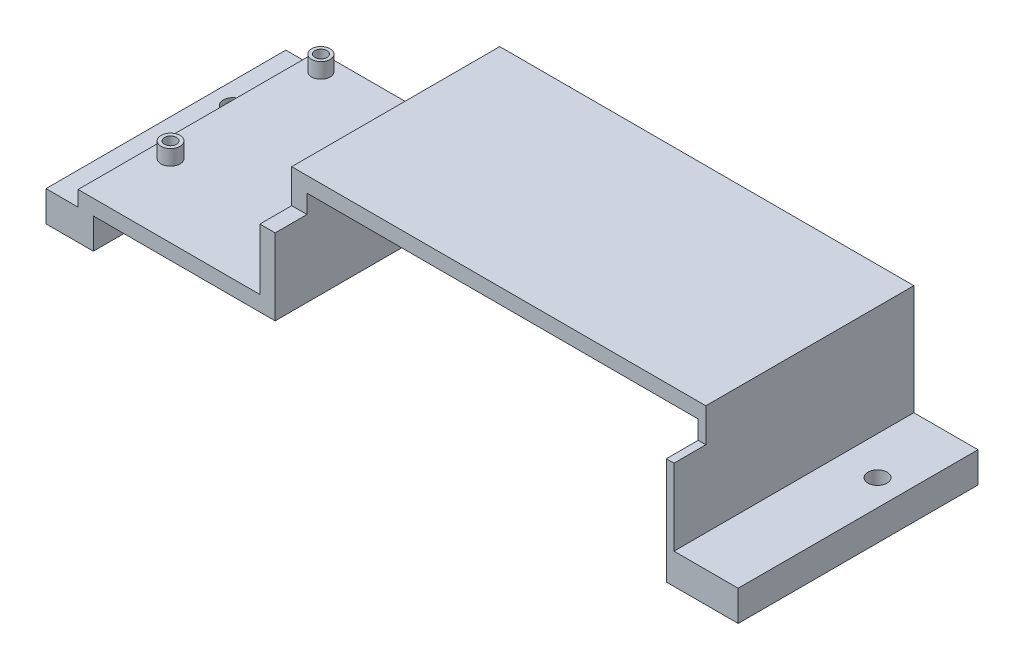
SolidWorks part; units mm, degrees
ref_plane "Front Plane" through (0, 0, 0) normal (0, 0, 1) x (1, 0, 0)
ref_plane "Top Plane" through (0, 0, 0) normal (0, 1, 0) x (1, 0, 0)
ref_plane "Right Plane" through (0, 0, 0) normal (1, 0, 0) x (0, 0, -1)
sketch "Sketch2" plane through (0, 0, 0) normal (0, 0, 1) x (1, 0, 0)
  line L0 (-30.226, 0) -> (-30.226, -5.08)
  line L1 (-30.226, -5.08) -> (-38.1, -5.08)
  line L2 (-38.1, -5.08) -> (-38.1, 0)
  line L3 (-38.1, 0) -> (-32.766, 0)
  line L4 (-32.766, 0) -> (-32.766, 2.54)
  line L5 (-32.766, 2.54) -> (-2.54, 2.54)
  line L6 (-2.54, 2.54) -> (-2.54, 18.288)
  line L7 (-2.54, 18.288) -> (66.31, 18.288)
  line L8 (66.31, 18.288) -> (66.31, 0)
  line L9 (66.31, 0) -> (76.978, 0)
  line L10 (76.978, 0) -> (76.978, -5.08)
  line L11 (76.978, -5.08) -> (65.04, -5.08)
  line L12 (65.04, -5.08) -> (65.04, 15.748)
  line L13 (65.04, 15.748) -> (0, 15.748)
  line L14 (0, 15.748) -> (0, 0)
  line L15 (0, 0) -> (-30.226, 0)
  point P14 (65.04, 5.334)
  point P18 (-34.163, -5.08)
  dimension "D1" = 2.54
  dimension "D2" = 2.54
  dimension "D3" = 1.27
  dimension "D4" = 2.54
  dimension "D5" = 15.748
  dimension "D6" = 65.04
  dimension "D7" = 5.08
  dimension "D8" = 5.08
  dimension "D9" = 27.686
  dimension "D10" = 2.54
  dimension "D11" = 11.938
  dimension "D12" = 7.874
extrude "Boss-Extrude1" add sketch "Sketch2" along normal blind 39.878
sketch "Sketch3" plane through (0, -5.08, 0) normal (0, -1, 0) x (1, 0, 0)
  circle A0 centre (-34.544, 12.3691) radius 1.5875
  circle A1 centre (72.644, 12.3691) radius 1.5875
extrude "Cut-Extrude1" cut sketch "Sketch3" against normal through all
sketch "Sketch5" plane through (76.978, 0, 0) normal (1, 0, 0) x (0, 0, -1)
  line L1 (-39.878, 18.288) -> (-34.5826, 18.288)
  line L2 (-39.878, 18.288) -> (-39.878, 12.6751)
  line L3 (-39.878, 12.6751) -> (-34.5826, 12.6751)
  line L4 (-34.5826, 18.288) -> (-34.5826, 12.6751)
extrude "Cut-Extrude2" cut sketch "Sketch5" against normal through all
sketch "Sketch6" plane through (0, 2.54, 0) normal (0, 1, 0) x (1, 0, 0)
  circle A0 centre (-29.54, -27.73) radius 1
  circle A1 centre (-29.54, -2.73) radius 1
  circle A2 centre (-4.54, -2.73) radius 1
  circle A3 centre (-4.54, -27.73) radius 1
  circle A4 centre (-29.54, -27.73) radius 1.5768
  circle A5 centre (-29.54, -2.73) radius 1.5369
  circle A6 centre (-4.54, -27.73) radius 1.5746
  circle A7 centre (-4.54, -2.73) radius 1.6269
extrude "Boss-Extrude3" add sketch "Sketch6" along normal blind 2.54
